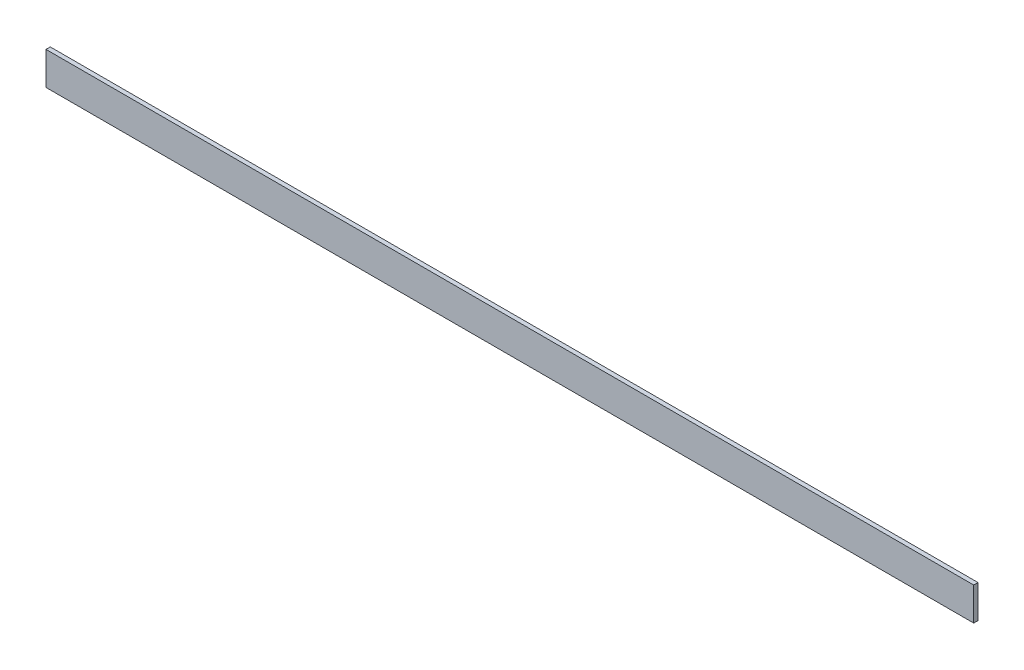
SolidWorks part; units mm, degrees
material "6061-T6 (SS)"
ref_plane "Front Plane" through (0, 0, 0) normal (0, 0, 1) x (1, 0, 0)
ref_plane "Top Plane" through (0, 0, 0) normal (0, 1, 0) x (1, 0, 0)
ref_plane "Right Plane" through (0, 0, 0) normal (1, 0, 0) x (0, 0, -1)
sketch "Sketch1" plane through (0, 0, 0) normal (0, 0, 1) x (1, 0, 0)
  line L1 (0, 0) -> (714.502, 0)
  line L2 (0, 0) -> (0, 25.4)
  line L3 (0, 25.4) -> (714.502, 25.4)
  line L4 (714.502, 0) -> (714.502, 25.4)
  point P5 (0, 0)
  dimension "D1" = 714.502
  dimension "D2" = 25.4
extrude "Boss-Extrude1" add sketch "Sketch1" along normal blind 3.302
equation "\"Load\" = 400"
equation "\"Modulus\" = 10000000"
equation "\"Max Deflection\"= 0.009"
equation "\"Width\" = 1"
equation "\"Bar Thickness\" = 0.125"
equation "\"Area\"= \"Width\" * \"Bar Thickness\""
equation "\"Length\"= \"Max Deflection\" * \"Area\" * \"Modulus\" / \"Load\""
